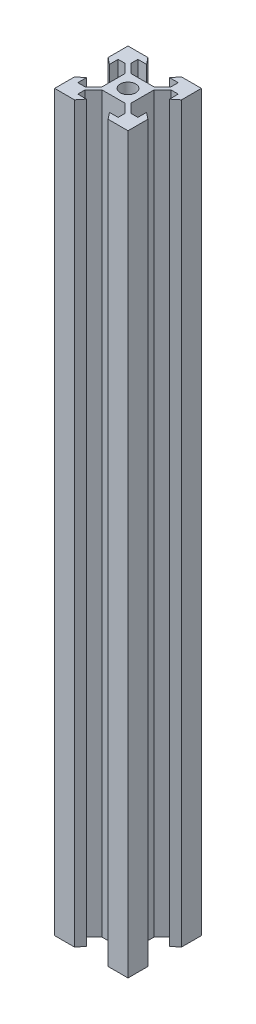
SolidWorks part; units mm, degrees
ref_plane "Front Plane" through (0, 0, 0) normal (0, 0, 1) x (1, 0, 0)
ref_plane "Top Plane" through (0, 0, 0) normal (0, 1, 0) x (1, 0, 0)
ref_plane "Right Plane" through (0, 0, 0) normal (1, 0, 0) x (0, 0, -1)
sketch "Sketch1" plane through (0, 0, 0) normal (0, 1, 0) x (1, 0, 0)
  line L0 (0, 0) -> (5.42, 0)
  line L2 (20, 20) -> (14.58, 20)
  line L3 (0, 20) -> (0, 14.58)
  line L5 (0, 5.415) -> (1.8, 6.875)
  line L6 (15.5, 18.2) -> (13.125, 18.2)
  line L7 (6.1, 6.85) -> (6.1, 13.15)
  line L8 (1.8, 15.5) -> (1.8, 13.12)
  line L10 (4.5, 1.8) -> (6.875, 1.8)
  line L12 (18.2, 4.5) -> (18.2, 5.415)
  line L17 (13.1475, 1.8) -> (15.5, 1.8)
  line L18 (13.9, 13.15) -> (13.9, 6.85)
  line L21 (13.15, 13.9) -> (6.85, 13.9)
  line L23 (6.85, 6.1) -> (13.15, 6.1)
  line L25 (6.875, 18.2) -> (4.5, 18.2)
  line L26 (0, 5.415) -> (0, 0)
  line L27 (6.1, 13.15) -> (3.75, 15.5)
  line L28 (6.85, 13.9) -> (4.5, 16.25)
  line L29 (13.15, 13.9) -> (15.5, 16.25)
  line L30 (15.5, 18.2) -> (13.125, 18.2)
  line L31 (4.5, 3.75) -> (6.85, 6.1)
  line L32 (6.1, 6.85) -> (3.75, 4.5)
  line L33 (0, 14.58) -> (0, 14.7)
  line L35 (18.2, 13.12) -> (18.2, 15.5)
  line L37 (16.25, 4.5) -> (13.9, 6.85)
  line L38 (15.5, 3.75) -> (13.15, 6.1)
  line L40 (5.42, 20) -> (0, 20)
  line L41 (13.9, 13.15) -> (16.25, 15.5)
  line L42 (18.2, 15.5) -> (18.2, 13.12)
  line L43 (14.58, 0) -> (20, 0)
  line L44 (14.58, 20) -> (20, 20)
  line L45 (1.8, 6.875) -> (1.8, 5.415)
  line L46 (5.42, 20) -> (6.875, 18.2)
  line L47 (13.125, 18.2) -> (14.58, 20)
  line L50 (14.58, 20) -> (20, 20)
  line L54 (5.42, 0) -> (6.875, 1.8)
  line L55 (18.2, 13.12) -> (18.2, 15.5)
  line L56 (13.1475, 1.8) -> (14.58, 0)
  line L57 (15.5, 18.2) -> (13.125, 18.2)
  line L58 (4.5, 18.2) -> (6.875, 18.2)
  line L59 (1.8, 15.5) -> (1.8, 13.12)
  line L60 (4.5, 18.2) -> (6.875, 18.2)
  line L61 (1.8, 15.5) -> (1.8, 13.12)
  line L62 (5.42, 20) -> (6.875, 18.2)
  line L63 (1.8, 13.12) -> (1.8, 14.7)
  line L64 (18.2, 5.415) -> (18.2, 4.5)
  line L65 (4.5, 18.2) -> (6.875, 18.2)
  line L69 (1.8, 13.12) -> (1.8, 13.125)
  line L70 (20, 5.415) -> (20, 0)
  line L71 (1.8, 14.7) -> (1.8, 13.12)
  line L72 (1.8, 13.12) -> (1.8, 13.125)
  line L73 (0, 5.415) -> (1.8, 6.875)
  line L74 (13.1475, 1.8) -> (15.5, 1.8)
  line L75 (14.58, 20) -> (20, 20)
  line L79 (1.8, 14.7) -> (1.8, 15.5)
  line L80 (5.42, 0) -> (6.875, 1.8)
  line L81 (15.5, 18.2) -> (13.125, 18.2)
  line L82 (1.8, 15.5) -> (1.8, 14.58)
  line L83 (18.2, 15.5) -> (18.2, 13.12)
  line L84 (15.5, 1.8) -> (13.1475, 1.8)
  line L85 (1.8, 14.58) -> (1.8, 13.125)
  line L86 (18.2, 13.12) -> (20, 14.58)
  line L87 (1.8, 13.125) -> (0, 14.58)
  line L89 (1.8, 13.125) -> (1.8, 13.12)
  line L91 (1.8, 14.58) -> (1.8, 13.12)
  line L92 (1.8, 14.58) -> (1.8, 13.12)
  line L94 (1.8, 14.58) -> (1.8, 13.12)
  line L98 (0, 20) -> (4.5, 20)
  line L99 (1.8, 5.415) -> (1.8, 4.5)
  line L100 (18.2, 6.85) -> (18.2, 6.8625)
  line L101 (18.2, 4.5) -> (18.2, 5.415)
  line L102 (18.2154, 6.8625) -> (18.2, 6.8625)
  line L108 (1.8, 13.12) -> (1.8, 13.125)
  line L110 (6.85, 13.9) -> (13.15, 13.9)
  line L111 (18.2, 6.85) -> (18.2, 6.8625)
  line L112 (4.5, 18.2) -> (4.5, 16.25)
  line L113 (18.2, 5.415) -> (18.2, 6.8625)
  line L114 (3.75, 15.5) -> (1.8, 15.5)
  line L115 (20, 5.415) -> (18.2, 6.85)
  line L116 (1.8, 15.5) -> (3.75, 15.5)
  line L117 (20, 20) -> (20, 14.58)
  line L118 (6.1, 13.15) -> (6.1, 6.85)
  line L119 (6.85, 6.1) -> (13.15, 6.1)
  line L120 (20, 14.58) -> (20, 20)
  line L121 (0, 20) -> (4.5, 20)
  line L122 (20, 20) -> (15.5, 20)
  line L125 (15.5, 18.2) -> (15.5, 16.25)
  line L128 (20, 0) -> (20, 4.5)
  line L131 (1.8, 5.415) -> (1.8, 4.5)
  line L132 (6.875, 1.8) -> (4.5, 1.8)
  line L133 (4.5, 1.8) -> (6.875, 1.8)
  line L134 (18.2, 4.5) -> (16.25, 4.5)
  line L135 (15.5, 3.75) -> (15.5, 1.8)
  line L136 (6.875, 1.8) -> (4.5, 1.8)
  line L137 (0, 0) -> (4.5, 0)
  line L138 (4.5, 1.8) -> (4.5, 3.75)
  line L139 (3.75, 4.5) -> (1.8, 4.5)
  line L140 (16.25, 15.5) -> (18.2, 15.5)
  circle A0 centre (10, 10) radius 2.1
extrude "Boss-Extrude1" add sketch "Sketch1" along normal blind 200 contours L41 L140 L35 L86 L117 L2 L75 L47 L6 L125 L29 L21 L28 L112 L25 L46 L40 L3 L87 L71 L61 L8 L114 L27 L7 L32 L139 L99 L45 L5 L26 L0 L54 L10 L138 L31 L23 L38 L135 L17 L56 L43 L70 L115 L113 L12 L134
